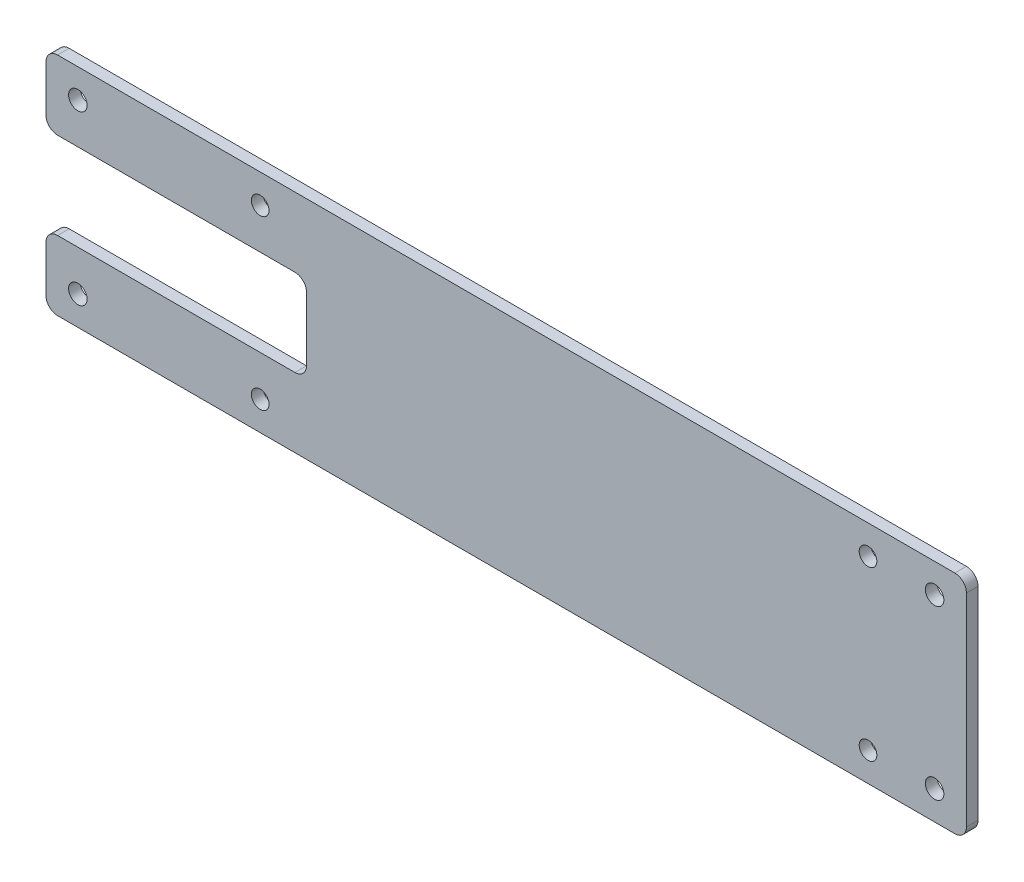
SolidWorks part; units mm, degrees
material "环氧树脂,未充填"
ref_plane "前视基准面" through (0, 0, 0) normal (0, 0, 1) x (1, 0, 0)
ref_plane "上视基准面" through (0, 0, 0) normal (0, 1, 0) x (1, 0, 0)
ref_plane "右视基准面" through (0, 0, 0) normal (1, 0, 0) x (0, 0, -1)
other "Configuration Table"
sketch "草图1" plane through (0, 0, 0) normal (0, 0, 1) x (1, 0, 0)
  line L0 (-57.5, -19.5) -> (-57.5, 19.5)
  line L1 (-52.5, -14.5) -> (52.5, -14.5) construction
  line L2 (-52.5, -14.5) -> (-52.5, 14.5) construction
  line L3 (-52.5, 14.5) -> (52.5, 14.5) construction
  line L4 (52.5, -14.5) -> (52.5, 14.5) construction
  line L5 (-52.5, -14.5) -> (52.5, 14.5) construction
  line L6 (-52.5, 14.5) -> (52.5, -14.5) construction
  line L7 (-57.5, 19.5) -> (57.5, 19.5)
  line L8 (57.5, -19.5) -> (57.5, 19.5)
  line L9 (-57.5, -19.5) -> (57.5, -19.5)
  line L10 (0, 0) -> (50000, 0) construction
  line L12 (69.5, -19.5) -> (-89.5, -19.5)
  line L13 (69.5, -19.5) -> (69.5, 19.5)
  line L14 (69.5, 19.5) -> (-89.5, 19.5)
  line L15 (-89.5, -19.5) -> (-89.5, 19.5)
  line L16 (69.5, -19.5) -> (-89.5, 19.5) construction
  line L17 (69.5, 19.5) -> (-89.5, -19.5) construction
  line L18 (64, -14.5) -> (-84, -14.5) construction
  line L19 (64, -14.5) -> (64, 14.5) construction
  line L20 (64, 14.5) -> (-84, 14.5) construction
  line L21 (-84, -14.5) -> (-84, 14.5) construction
  line L22 (64, -14.5) -> (-84, 14.5) construction
  line L23 (64, 14.5) -> (-84, -14.5) construction
  circle A0 centre (-52.5, 14.5) radius 1.525
  circle A1 centre (-52.5, -14.5) radius 1.525
  circle A2 centre (52.5, -14.5) radius 1.525
  circle A3 centre (52.5, 14.5) radius 1.525
  circle A4 centre (-84, 14.5) radius 1.6
  circle A5 centre (-84, -14.5) radius 1.6
  circle A6 centre (64, 14.5) radius 1.6
  circle A7 centre (64, -14.5) radius 1.6
  point P0 (0, 0)
  point P16 (-10, 0)
  point P22 (-10, 0)
  dimension "D4" = 3.05
  dimension "D5" = 3.2
  dimension "D6" = 5.5
  dimension "D1" = 105
  dimension "D2" = 29
  dimension "D7" = 148
  dimension "D8" = 29
  dimension "D9" = 10
  dimension "D3" = 5
extrude "凸台-拉伸1" add sketch "草图1" along normal blind 2 contours L15 L12 L0 L14 A5 A4 | L0 L9 L8 L7 A3 A2 A1 A0 | L13 L14 L8 L12 A7 A6
sketch "草图2" plane through (0, 0, 2) normal (0, 0, 1) x (1, 0, 0)
  line L0 (-84, 14.5) -> (-57.5, 14.5) construction
  line L1 (-57.5, 14.5) -> (-57.5, 0) construction
  line L2 (-57.5, 0) -> (0, 0) construction
  line L3 (-89.5, -19.5) -> (-89.5, 19.5) construction
  line L4 (-70.5, -7.5) -> (-44.5, -7.5)
  line L5 (-70.5, -7.5) -> (-70.5, 7.5)
  line L6 (-70.5, 7.5) -> (-44.5, 7.5)
  line L7 (-44.5, -7.5) -> (-44.5, 7.5)
  line L8 (-70.5, -7.5) -> (-44.5, 7.5) construction
  line L9 (-70.5, 7.5) -> (-44.5, -7.5) construction
  line L10 (-70.5, 7.5) -> (-89.5, 7.5)
  line L11 (-70.5, 7.5) -> (-70.5, -7.5)
  line L12 (-70.5, -7.5) -> (-89.5, -7.5)
  line L13 (-89.5, 7.5) -> (-89.5, -7.5)
  line M3 (-89.5, 19.5) -> (-89.5, -19.5)
  dimension "D1" = 26.5
  dimension "D2" = 15
  dimension "D3" = 26
extrude "切除-拉伸1" cut sketch "草图2" against normal blind 10 contours L12 L5 L10 M3 | L4 L7 L6 L5
fillet "圆角1" radius 2 8 edges at (-89.5, -7.5, 1) (-89.5, -19.5, 1) (69.5, -19.5, 1) (69.5, 19.5, 1) (-89.5, 19.5, 1) (-89.5, 7.5, 1) (-44.5, -7.5, 1) (-44.5, 7.5, 1)
